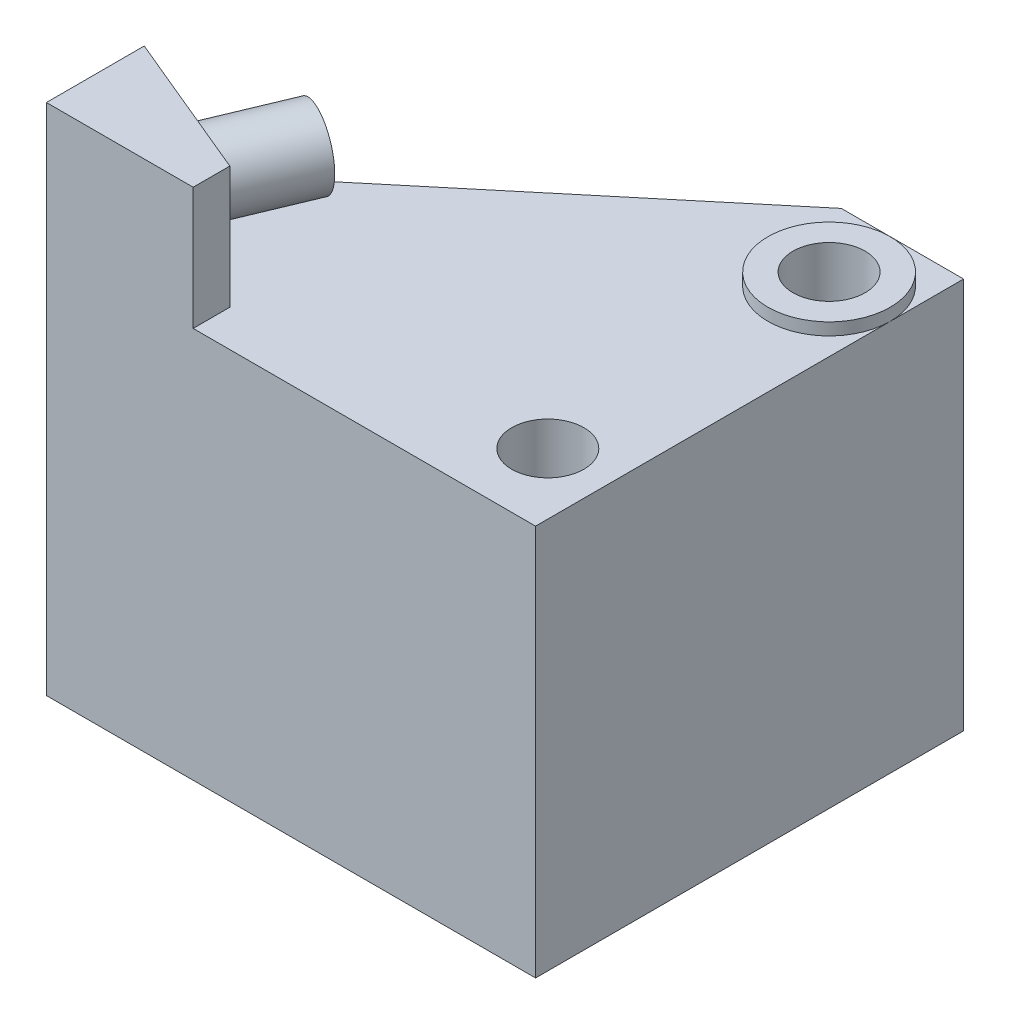
SolidWorks part; units mm, degrees
ref_plane "Спереди" through (0, 0, 0) normal (0, 0, 1) x (1, 0, 0)
ref_plane "Сверху" through (0, 0, 0) normal (0, 1, 0) x (1, 0, 0)
ref_plane "Справа" through (0, 0, 0) normal (1, 0, 0) x (0, 0, -1)
sketch "Эскиз2" plane through (0, 0, 0) normal (0, 1, 0) x (1, 0, 0)
  line L0 (-20, 5) -> (-5, 17.5)
  line L5 (-5, 17.5) -> (0, 17.5)
  line L6 (0, 17.5) -> (0, 0)
  line L7 (0, 0) -> (-20, 0)
  line L8 (-20, 0) -> (-20, 5)
  dimension "D1" = 5
  dimension "D2" = 17.5
  dimension "D3" = 20
extrude "Бобышка-Вытянуть1" add sketch "Эскиз2" along normal blind 16
sketch "Эскиз3" plane through (0, 16, 0) normal (0, 1, 0) x (1, 0, 0)
  line L0 (-2.5, -975) -> (-2.5, 49025) construction
  line L1 (0, 17.5) -> (-5, 17.5) construction
  line L2 (-20, 0) -> (0, 0) construction
  circle A0 centre (-2.5, 14.5) radius 1.475
  circle A1 centre (-2.5, 3) radius 1.475
  point P5 (-2.5, 17.5)
  dimension "D1" = 2.95
  dimension "D2" = 3
  dimension "D3" = 3
extrude "Вырез-Вытянуть1" cut sketch "Эскиз3" against normal through all
sketch "Эскиз4" plane through (0, 16, 0) normal (0, 1, 0) x (1, 0, 0)
  line L0 (-20, 4) -> (-20, 0)
  line L1 (-20, 0) -> (-14, 0)
  line L2 (-20, 0) -> (0, 0) construction
  line L4 (-14, 0) -> (-14, 1.5)
  line L5 (-14, 1.5) -> (-20, 4)
  dimension "D1" = 4
  dimension "D2" = 6
  dimension "D3" = 1.5
extrude "Бобышка-Вытянуть2" add sketch "Эскиз4" along normal blind 5
sketch "Эскиз5" plane through (0, 16, 0) normal (0, 1, 0) x (1, 0, 0)
  line L0 (0, 0) -> (0, 17.5) construction
  circle A0 centre (-2.5, 14.5) radius 2.5
  circle A1 centre (-2.5, 14.5) radius 1.475
  circle A2 centre (-2.5, 14.5) radius 1.475 construction
extrude "Бобышка-Вытянуть3" add sketch "Эскиз5" along normal blind 0.5
sketch "Эскиз6" plane through (-1.5385, 0, 3.6923) normal (0.3846, 0, -0.9231) x (-0.9231, 0, -0.3846)
  line L0 (16.75, -979) -> (16.75, 49021) construction
  line L2 (13.5, 21) -> (20, 21) construction
  line L4 (-980.3226, 18.5) -> (49019.6774, 18.5) construction
  line L5 (20, 21) -> (20, 16) construction
  circle A0 centre (16.75, 18.5) radius 1.5
  point P5 (16.75, 21)
  point P13 (20, 18.5)
  dimension "D1" = 3
extrude "Бобышка-Вытянуть4" add sketch "Эскиз6" along normal blind 4
